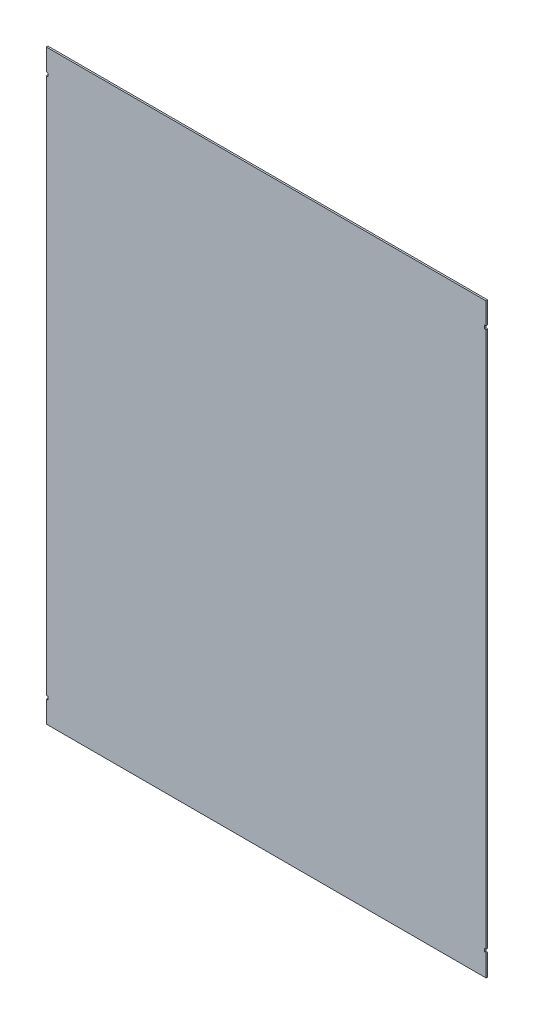
SolidWorks part; units mm, degrees
material "Acrylic (Medium-high impact)"
ref_plane "Front Plane" through (0, 0, 0) normal (0, 0, 1) x (1, 0, 0)
ref_plane "Top Plane" through (0, 0, 0) normal (0, 1, 0) x (1, 0, 0)
ref_plane "Right Plane" through (0, 0, 0) normal (1, 0, 0) x (0, 0, -1)
sketch "Sketch1" plane through (0, 0, 0) normal (0, 0, 1) x (1, 0, 0)
  line L1 (0, 0) -> (838.2, 0)
  line L2 (0, 0) -> (0, 1117.6)
  line L3 (0, 1117.6) -> (838.2, 1117.6)
  line L4 (838.2, 0) -> (838.2, 1117.6)
  dimension "D1" = 838.2
  dimension "D2" = 1117.6
extrude "Boss-Extrude1" add sketch "Sketch1" along normal blind 3.175
sketch "Sketch3" plane through (0, 0, 3.175) normal (0, 0, 1) x (1, 0, 0)
  line L0 (0, 1117.6) -> (0, 0) construction
  line L1 (0, 1076.3455) -> (3.175, 1076.3455)
  line L2 (0, 1076.3455) -> (0, 1069.9955)
  line L3 (0, 1069.9955) -> (3.175, 1069.9955)
  line L4 (3.175, 1076.3455) -> (3.175, 1069.9955)
  line L5 (3.175, 0) -> (3.175, 41.2545) construction
  dimension "D1" = 6.35
extrude "Cut-Extrude2" cut sketch "Sketch3" against normal blind 25.4
ref_plane "Plane1" through (0, 558.8, 0) normal (0, 1, 0) x (1, 0, 0)
mirror "Mirror1" about plane through (0, 558.8, 0) normal (0, 1, 0) of "Cut-Extrude2"
ref_plane "Plane2" through (419.1, 0, 0) normal (-1, 0, 0) x (0, 0, 1)
mirror "Mirror3" about plane through (419.1, 0, 0) normal (-1, 0, 0) of "Mirror1", "Cut-Extrude2"
equation "\"L\"= 33in'length"
equation "\"W\"= 44in'width"
equation "\"t\"= 1 / 8in'thickness"
equation "\"D1@Sketch1\"=\"L\""
equation "\"D2@Sketch1\"=\"W\""
equation "\"D1@Boss-Extrude1\"=\"t\""
